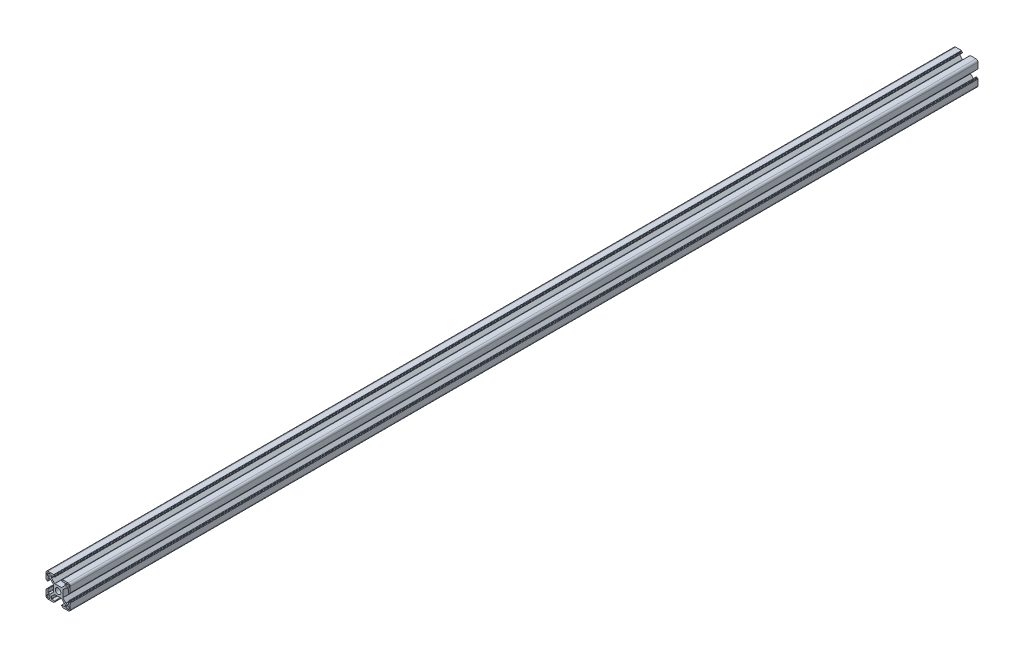
SolidWorks part; units mm, degrees
ref_plane "Front Plane" through (0, 0, 0) normal (0, 0, 1) x (1, 0, 0)
ref_plane "Top Plane" through (0, 0, 0) normal (0, 1, 0) x (1, 0, 0)
ref_plane "Right Plane" through (0, 0, 0) normal (1, 0, 0) x (0, 0, -1)
sketch "Model" plane through (0, 0, 0) normal (0, 0, 1) x (1, 0, 0)
  line L0 (21.5, 27) -> (25, 27)
  line L1 (27, 25) -> (27, 21.5)
  line L2 (25, 19.5) -> (21.5, 19.5)
  line L3 (19.5, 21.5) -> (19.5, 25)
  line L4 (21.5, -27) -> (25, -27)
  line L5 (27, -25) -> (27, -21.5)
  line L6 (25, -19.5) -> (21.5, -19.5)
  line L7 (19.5, -21.5) -> (19.5, -25)
  line L8 (0, 11.6) -> (-8.2402, 11.6)
  line L9 (-8.6645, 11.7757) -> (-16.3243, 19.4355)
  line L10 (-16.5, 19.8598) -> (-16.5, 25)
  line L11 (-15.9, 25.6) -> (-8.8, 25.6)
  line L12 (-8.2, 26.2) -> (-8.2, 27.4)
  line L13 (-8.8, 28) -> (-9.8, 28)
  line L14 (-10.4, 28.6) -> (-10.4, 29.4)
  line L15 (-11, 30) -> (-25, 30)
  line L16 (-30, 25) -> (-30, 11)
  line L17 (-29.4, 10.4) -> (-28.6, 10.4)
  line L18 (-28, 9.8) -> (-28, 8.8)
  line L19 (-27.4, 8.2) -> (-26.2, 8.2)
  line L20 (-25.6, 8.8) -> (-25.6, 15.9)
  line L21 (-25, 16.5) -> (-19.8598, 16.5)
  line L22 (-19.4355, 16.3243) -> (-11.7757, 8.6645)
  line L23 (-11.6, 8.2402) -> (-11.6, 0)
  line L24 (-11.6, 0) -> (-11.6, -8.2402)
  line L25 (-11.7757, -8.6645) -> (-19.4355, -16.3243)
  line L26 (-19.8598, -16.5) -> (-25, -16.5)
  line L27 (-25.6, -15.9) -> (-25.6, -8.8)
  line L28 (-26.2, -8.2) -> (-27.4, -8.2)
  line L29 (-28, -8.8) -> (-28, -9.8)
  line L30 (-28.6, -10.4) -> (-29.4, -10.4)
  line L31 (-30, -11) -> (-30, -25)
  line L32 (-25, -30) -> (-11, -30)
  line L33 (-10.4, -29.4) -> (-10.4, -28.6)
  line L34 (-9.8, -28) -> (-8.8, -28)
  line L35 (-8.2, -27.4) -> (-8.2, -26.2)
  line L36 (-8.8, -25.6) -> (-15.9, -25.6)
  line L37 (-16.5, -25) -> (-16.5, -19.8598)
  line L38 (-16.3243, -19.4355) -> (-8.6645, -11.7757)
  line L39 (-8.2402, -11.6) -> (0, -11.6)
  line L40 (0, -11.6) -> (8.2402, -11.6)
  line L41 (8.6645, -11.7757) -> (16.3243, -19.4355)
  line L42 (16.5, -19.8598) -> (16.5, -25)
  line L43 (15.9, -25.6) -> (8.8, -25.6)
  line L44 (8.2, -26.2) -> (8.2, -27.4)
  line L45 (8.8, -28) -> (9.8, -28)
  line L46 (10.4, -28.6) -> (10.4, -29.4)
  line L47 (11, -30) -> (25, -30)
  line L48 (30, -25) -> (30, -11)
  line L49 (29.4, -10.4) -> (28.6, -10.4)
  line L50 (28, -9.8) -> (28, -8.8)
  line L51 (27.4, -8.2) -> (26.2, -8.2)
  line L52 (25.6, -8.8) -> (25.6, -15.9)
  line L53 (25, -16.5) -> (19.8598, -16.5)
  line L54 (19.4355, -16.3243) -> (11.7757, -8.6645)
  line L55 (11.6, -8.2402) -> (11.6, 0)
  line L56 (11.6, 0) -> (11.6, 8.2402)
  line L57 (11.7757, 8.6645) -> (19.6113, 16.5)
  line L58 (19.6113, 16.5) -> (25, 16.5)
  line L59 (25.6, 15.9) -> (25.6, 8.8)
  line L60 (26.2, 8.2) -> (27.4, 8.2)
  line L61 (28, 8.8) -> (28, 9.8)
  line L62 (28.6, 10.4) -> (29.4, 10.4)
  line L63 (30, 11) -> (30, 25)
  line L64 (25, 30) -> (11, 30)
  line L65 (10.4, 29.4) -> (10.4, 28.6)
  line L66 (9.8, 28) -> (8.8, 28)
  line L67 (8.2, 27.4) -> (8.2, 26.2)
  line L68 (8.8, 25.6) -> (15.9, 25.6)
  line L69 (16.5, 25) -> (16.5, 19.8598)
  line L70 (16.3243, 19.4355) -> (8.6645, 11.7757)
  line L71 (8.2402, 11.6) -> (0, 11.6)
  line L72 (-21.5, -27) -> (-25, -27)
  line L73 (-27, -25) -> (-27, -21.5)
  line L74 (-25, -19.5) -> (-21.5, -19.5)
  line L75 (-19.5, -21.5) -> (-19.5, -25)
  line L76 (-21.5, 27) -> (-25, 27)
  line L77 (-27, 25) -> (-27, 21.5)
  line L78 (-25, 19.5) -> (-21.5, 19.5)
  line L79 (-19.5, 21.5) -> (-19.5, 25)
  circle A0 centre (0, 0) radius 6.8
  arc A1 (21.5, 27) -> (19.5, 25) centre (21.5, 25) ccw
  arc A2 (27, 25) -> (25, 27) centre (25, 25) ccw
  arc A3 (25, 19.5) -> (27, 21.5) centre (25, 21.5) ccw
  arc A4 (19.5, 21.5) -> (21.5, 19.5) centre (21.5, 21.5) ccw
  arc A5 (19.5, -25) -> (21.5, -27) centre (21.5, -25) ccw
  arc A6 (25, -27) -> (27, -25) centre (25, -25) ccw
  arc A7 (27, -21.5) -> (25, -19.5) centre (25, -21.5) ccw
  arc A8 (21.5, -19.5) -> (19.5, -21.5) centre (21.5, -21.5) ccw
  arc A9 (-8.6645, 11.7757) -> (-8.2402, 11.6) centre (-8.2402, 12.2) ccw
  arc A10 (-16.5, 19.8598) -> (-16.3243, 19.4355) centre (-15.9, 19.8598) ccw
  arc A11 (-15.9, 25.6) -> (-16.5, 25) centre (-15.9, 25) ccw
  arc A12 (-8.8, 25.6) -> (-8.2, 26.2) centre (-8.8, 26.2) ccw
  arc A13 (-8.2, 27.4) -> (-8.8, 28) centre (-8.8, 27.4) ccw
  arc A14 (-10.4, 28.6) -> (-9.8, 28) centre (-9.8, 28.6) ccw
  arc A15 (-10.4, 29.4) -> (-11, 30) centre (-11, 29.4) ccw
  arc A16 (-25, 30) -> (-30, 25) centre (-25, 25) ccw
  arc A17 (-30, 11) -> (-29.4, 10.4) centre (-29.4, 11) ccw
  arc A18 (-28, 9.8) -> (-28.6, 10.4) centre (-28.6, 9.8) ccw
  arc A19 (-28, 8.8) -> (-27.4, 8.2) centre (-27.4, 8.8) ccw
  arc A20 (-26.2, 8.2) -> (-25.6, 8.8) centre (-26.2, 8.8) ccw
  arc A21 (-25, 16.5) -> (-25.6, 15.9) centre (-25, 15.9) ccw
  arc A22 (-19.4355, 16.3243) -> (-19.8598, 16.5) centre (-19.8598, 15.9) ccw
  arc A23 (-11.6, 8.2402) -> (-11.7757, 8.6645) centre (-12.2, 8.2402) ccw
  arc A24 (-11.7757, -8.6645) -> (-11.6, -8.2402) centre (-12.2, -8.2402) ccw
  arc A25 (-19.8598, -16.5) -> (-19.4355, -16.3243) centre (-19.8598, -15.9) ccw
  arc A26 (-25.6, -15.9) -> (-25, -16.5) centre (-25, -15.9) ccw
  arc A27 (-25.6, -8.8) -> (-26.2, -8.2) centre (-26.2, -8.8) ccw
  arc A28 (-27.4, -8.2) -> (-28, -8.8) centre (-27.4, -8.8) ccw
  arc A29 (-28.6, -10.4) -> (-28, -9.8) centre (-28.6, -9.8) ccw
  arc A30 (-29.4, -10.4) -> (-30, -11) centre (-29.4, -11) ccw
  arc A31 (-30, -25) -> (-25, -30) centre (-25, -25) ccw
  arc A32 (-11, -30) -> (-10.4, -29.4) centre (-11, -29.4) ccw
  arc A33 (-9.8, -28) -> (-10.4, -28.6) centre (-9.8, -28.6) ccw
  arc A34 (-8.8, -28) -> (-8.2, -27.4) centre (-8.8, -27.4) ccw
  arc A35 (-8.2, -26.2) -> (-8.8, -25.6) centre (-8.8, -26.2) ccw
  arc A36 (-16.5, -25) -> (-15.9, -25.6) centre (-15.9, -25) ccw
  arc A37 (-16.3243, -19.4355) -> (-16.5, -19.8598) centre (-15.9, -19.8598) ccw
  arc A38 (-8.2402, -11.6) -> (-8.6645, -11.7757) centre (-8.2402, -12.2) ccw
  arc A39 (8.6645, -11.7757) -> (8.2402, -11.6) centre (8.2402, -12.2) ccw
  arc A40 (16.5, -19.8598) -> (16.3243, -19.4355) centre (15.9, -19.8598) ccw
  arc A41 (15.9, -25.6) -> (16.5, -25) centre (15.9, -25) ccw
  arc A42 (8.8, -25.6) -> (8.2, -26.2) centre (8.8, -26.2) ccw
  arc A43 (8.2, -27.4) -> (8.8, -28) centre (8.8, -27.4) ccw
  arc A44 (10.4, -28.6) -> (9.8, -28) centre (9.8, -28.6) ccw
  arc A45 (10.4, -29.4) -> (11, -30) centre (11, -29.4) ccw
  arc A46 (25, -30) -> (30, -25) centre (25, -25) ccw
  arc A47 (30, -11) -> (29.4, -10.4) centre (29.4, -11) ccw
  arc A48 (28, -9.8) -> (28.6, -10.4) centre (28.6, -9.8) ccw
  arc A49 (28, -8.8) -> (27.4, -8.2) centre (27.4, -8.8) ccw
  arc A50 (26.2, -8.2) -> (25.6, -8.8) centre (26.2, -8.8) ccw
  arc A51 (25, -16.5) -> (25.6, -15.9) centre (25, -15.9) ccw
  arc A52 (19.4355, -16.3243) -> (19.8598, -16.5) centre (19.8598, -15.9) ccw
  arc A53 (11.6, -8.2402) -> (11.7757, -8.6645) centre (12.2, -8.2402) ccw
  arc A54 (11.7757, 8.6645) -> (11.6, 8.2402) centre (12.2, 8.2402) ccw
  arc A55 (25.6, 15.9) -> (25, 16.5) centre (25, 15.9) ccw
  arc A56 (25.6, 8.8) -> (26.2, 8.2) centre (26.2, 8.8) ccw
  arc A57 (27.4, 8.2) -> (28, 8.8) centre (27.4, 8.8) ccw
  arc A58 (28.6, 10.4) -> (28, 9.8) centre (28.6, 9.8) ccw
  arc A59 (29.4, 10.4) -> (30, 11) centre (29.4, 11) ccw
  arc A60 (30, 25) -> (25, 30) centre (25, 25) ccw
  arc A61 (11, 30) -> (10.4, 29.4) centre (11, 29.4) ccw
  arc A62 (9.8, 28) -> (10.4, 28.6) centre (9.8, 28.6) ccw
  arc A63 (8.8, 28) -> (8.2, 27.4) centre (8.8, 27.4) ccw
  arc A64 (8.2, 26.2) -> (8.8, 25.6) centre (8.8, 26.2) ccw
  arc A65 (16.5, 25) -> (15.9, 25.6) centre (15.9, 25) ccw
  arc A66 (16.3243, 19.4355) -> (16.5, 19.8598) centre (15.9, 19.8598) ccw
  arc A67 (8.2402, 11.6) -> (8.6645, 11.7757) centre (8.2402, 12.2) ccw
  arc A68 (-21.5, -27) -> (-19.5, -25) centre (-21.5, -25) ccw
  arc A69 (-27, -25) -> (-25, -27) centre (-25, -25) ccw
  arc A70 (-25, -19.5) -> (-27, -21.5) centre (-25, -21.5) ccw
  arc A71 (-19.5, -21.5) -> (-21.5, -19.5) centre (-21.5, -21.5) ccw
  arc A72 (-19.5, 25) -> (-21.5, 27) centre (-21.5, 25) ccw
  arc A73 (-25, 27) -> (-27, 25) centre (-25, 25) ccw
  arc A74 (-27, 21.5) -> (-25, 19.5) centre (-25, 21.5) ccw
  arc A75 (-21.5, 19.5) -> (-19.5, 21.5) centre (-21.5, 21.5) ccw
extrude "Boss-Extrude1" add sketch "Model" along normal blind 2250
scale "Scale1" bodies to scale 101 scale about centroid uniform scaling yes scale factor 0.333333
